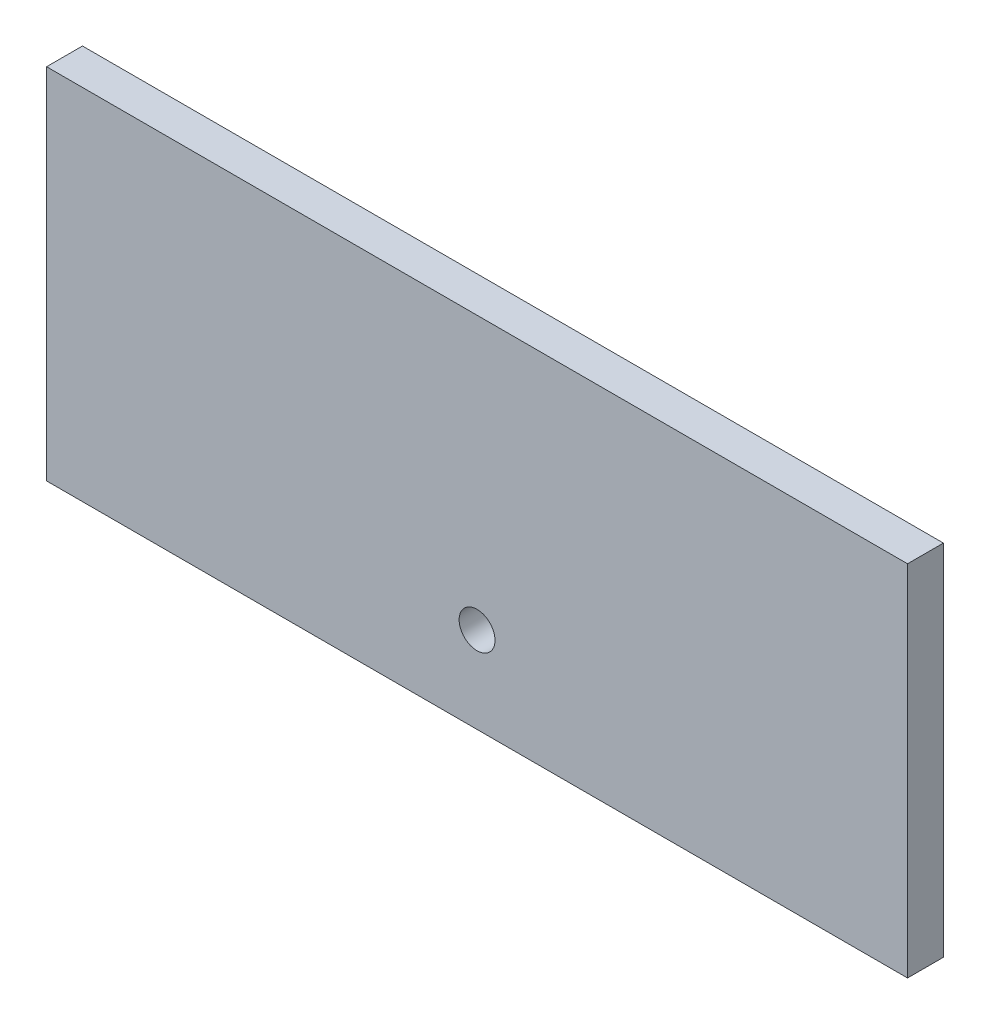
SolidWorks part; units mm, degrees
ref_plane "Front Plane" through (0, 0, 0) normal (0, 0, 1) x (1, 0, 0)
ref_plane "Top Plane" through (0, 0, 0) normal (0, 1, 0) x (1, 0, 0)
ref_plane "Right Plane" through (0, 0, 0) normal (1, 0, 0) x (0, 0, -1)
sketch "Sketch1" plane through (0, 0, 0) normal (0, 0, 1) x (1, 0, 0)
  line L1 (0, 0) -> (152.4, 0)
  line L2 (0, 0) -> (0, 63.5)
  line L3 (0, 63.5) -> (152.4, 63.5)
  line L4 (152.4, 0) -> (152.4, 63.5)
  circle A0 centre (76.2, 15.24) radius 3.175
  dimension "D3" = 6.35
  dimension "D4" = 15.24
  dimension "D1" = 63.5
  dimension "D2" = 152.4
  dimension "D5" = 76.2
extrude "Boss-Extrude1" add sketch "Sketch1" along normal blind 6.35
